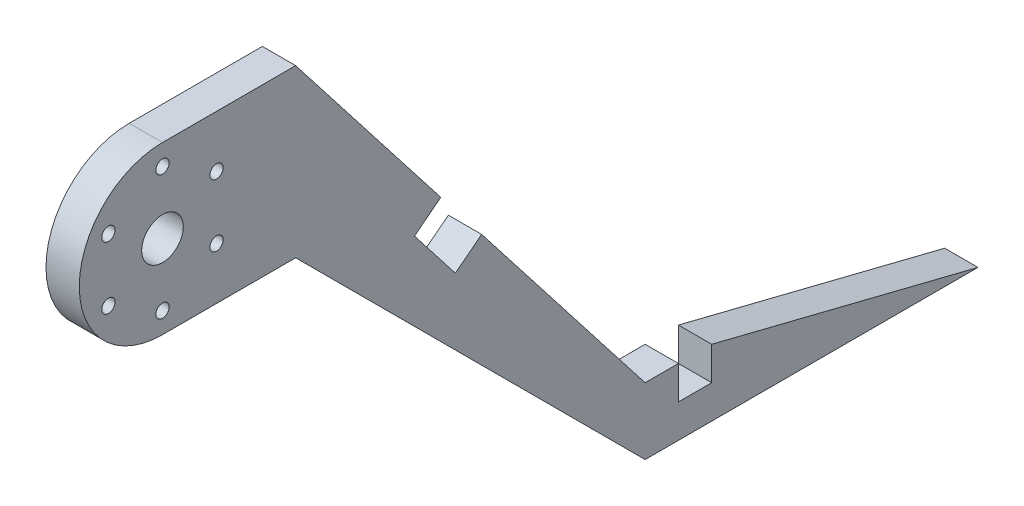
SolidWorks part; units mm, degrees
material "1023 Carbon Steel Sheet (SS)"
ref_plane "Front Plane" through (0, 0, 0) normal (0, 0, 1) x (1, 0, 0)
ref_plane "Top Plane" through (0, 0, 0) normal (0, 1, 0) x (1, 0, 0)
ref_plane "Right Plane" through (0, 0, 0) normal (1, 0, 0) x (0, 0, -1)
sketch "Sketch1" plane through (0, 0, 0) normal (1, 0, 0) x (0, 0, -1)
  line L1 (0, 31.75) -> (50.8, 31.75)
  line L2 (0, -31.75) -> (50.8, -31.75)
  line L4 (50.8, -31.75) -> (184.15, -165.1)
  line L6 (184.15, -139.7) -> (50.8, 31.75)
  line L11 (184.15, -165.1) -> (311.15, -165.1)
  line L12 (311.15, -165.1) -> (209.55, -139.7)
  line L13 (209.55, -139.7) -> (209.55, -152.4)
  line L14 (209.55, -152.4) -> (196.85, -152.4)
  line L15 (196.85, -152.4) -> (196.85, -139.7)
  line L16 (196.85, -139.7) -> (184.15, -139.7)
  arc A0 (0, 31.75) -> (0, -31.75) centre (0, 0) ccw
  dimension "D1" = 63.5
  dimension "D2" = 50.8
  dimension "D3" = 135
  dimension "D4" = 25.4
  dimension "D5" = 133.35
  dimension "D6" = 12.7
  dimension "D7" = 12.7
  dimension "D8" = 127
extrude "main" add sketch "Sketch1" along normal blind 12.7
sketch "Sketch2" plane through (12.7, 0, 0) normal (1, 0, 0) x (0, 0, -1)
  circle A0 centre (0, 0) radius 7.9375
  dimension "D1" = 15.875
extrude "axle" cut sketch "Sketch2" against normal up to surface (12.7 mm away) up to face at (0, -95.8273, -142.0091)
sketch "Sketch5" plane through (0, 36.5858, -47.0388) normal (0, 0.6139, -0.7894) x (-1, 0, 0)
  line L0 (-12.7, -223.3297) -> (-12.7, -6.1263) construction
  line L1 (-12.7, -96.3297) -> (0, -96.3297)
  line L2 (-12.7, -96.3297) -> (-12.7, -121.7297)
  line L3 (-12.7, -121.7297) -> (0, -121.7297)
  line L4 (0, -96.3297) -> (0, -121.7297)
  line L5 (0, -223.3297) -> (0, -6.1263) construction
  line L6 (-12.7, -223.3297) -> (0, -223.3297) construction
  point P8 (-6.35, -121.7297)
  dimension "D1" = 25.4
  dimension "D2" = 101.6
extrude "barwide" cut sketch "Sketch5" against normal blind 12.7
sketch "Sketch6" plane through (0, 0, 0) normal (-1, 0, 0) x (0, 0, 1)
  circle A1 centre (0, 23.8125) radius 2.54
  circle A2 centre (20.6222, 11.9062) radius 2.54
  circle A3 centre (20.6222, -11.9062) radius 2.54
  circle A4 centre (0, -23.8125) radius 2.54
  circle A5 centre (-20.6222, -11.9063) radius 2.54
  circle A6 centre (-20.6222, 11.9062) radius 2.54
  dimension "D1" = 5.08
  dimension "D2" = 23.8125
  dimension "D3" = 23.8125
  dimension "D4" = 23.8125
  dimension "D5" = 23.8125
  dimension "D6" = 23.8125
  dimension "D7" = 23.8125
  dimension "D8" = 23.8125
extrude "screws" cut sketch "Sketch6" against normal up to surface (12.7 mm away) up to face at (12.7, -84.5068, -133.1971)
equation "\"D4@Sketch6\"=\"D3@Sketch6\""
equation "\"D5@Sketch6\"=\"D3@Sketch6\""
equation "\"D6@Sketch6\"=\"D3@Sketch6\""
equation "\"D7@Sketch6\"=\"D3@Sketch6\""
equation "\"D8@Sketch6\"=\"D3@Sketch6\""
